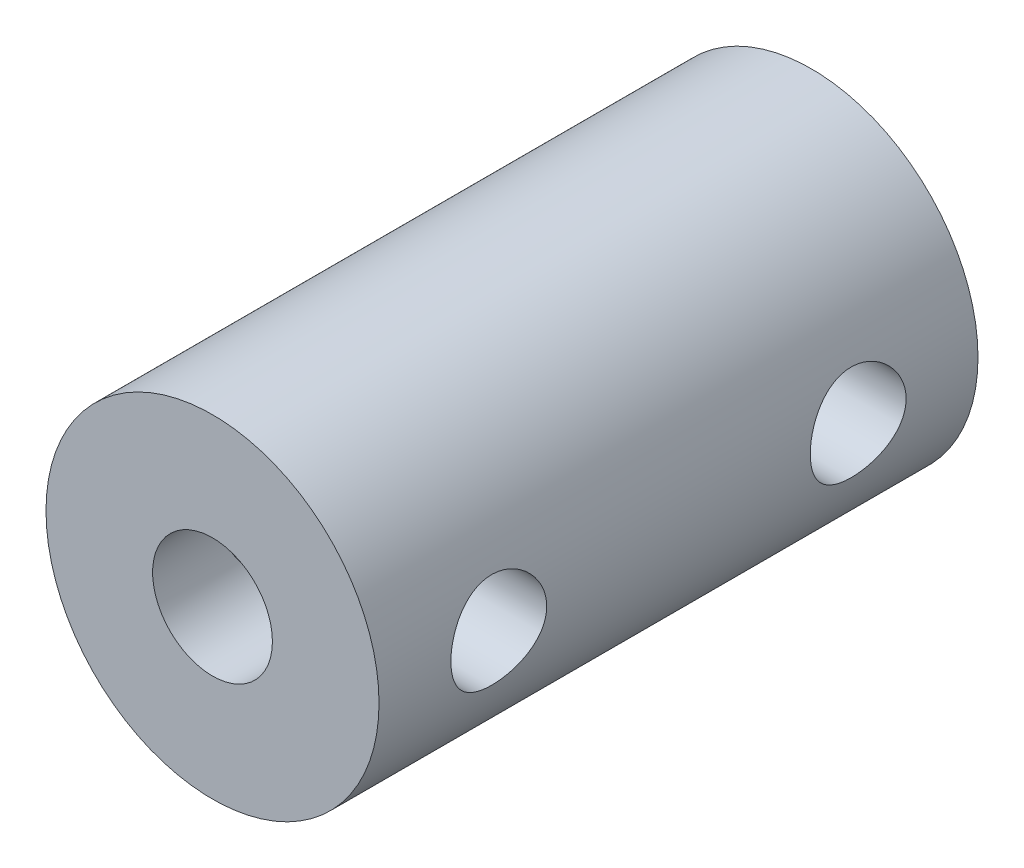
SolidWorks part; units mm, degrees
ref_plane "前视基准面" through (0, 0, 0) normal (0, 0, 1) x (1, 0, 0)
ref_plane "上视基准面" through (0, 0, 0) normal (0, 1, 0) x (1, 0, 0)
ref_plane "右视基准面" through (0, 0, 0) normal (1, 0, 0) x (0, 0, -1)
sketch "草图1" plane through (0, 0, 0) normal (0, 0, 1) x (1, 0, 0)
  circle A0 centre (0, 0) radius 2.5
  circle A1 centre (0, 0) radius 6.95
  dimension "D1" = 5
  dimension "D2" = 13.9
extrude "凸台-拉伸1" add sketch "草图1" along normal blind 25
ref_plane "基准面4" through (6.95, 0, 0) normal (1, 0, 0) x (0, 0, -1)
sketch "草图2" plane through (6.95, 0, 0) normal (1, 0, 0) x (0, 0, -1)
  line L0 (-12.5, 6.95) -> (-12.5, -6.95) construction
  line L1 (0, 6.95) -> (-25, 6.95) construction
  line L2 (-25, -6.95) -> (0, -6.95) construction
  line L3 (-12.5, 0) -> (-5, 0) construction
  circle A0 centre (-5, 0) radius 2
  circle A1 centre (-20, 0) radius 2
  dimension "D1" = 7.5
  dimension "D2" = 4
extrude "切除-拉伸1" cut sketch "草图2" against normal through all
